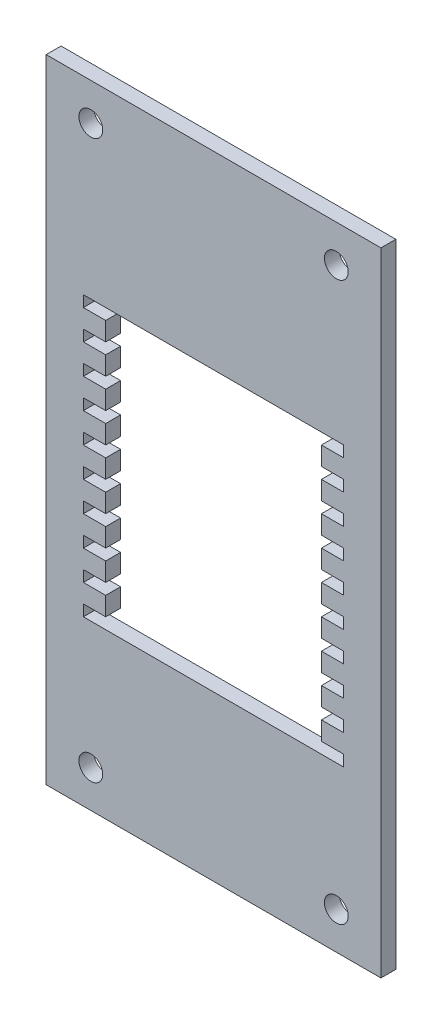
SolidWorks part; units mm, degrees
ref_plane "Ebene vorne" through (0, 0, 0) normal (0, 0, 1) x (1, 0, 0)
ref_plane "Ebene oben" through (0, 0, 0) normal (0, 1, 0) x (1, 0, 0)
ref_plane "Ebene rechts" through (0, 0, 0) normal (1, 0, 0) x (0, 0, -1)
sketch "Skizze1" plane through (0, 0, 0) normal (0, 0, 1) x (1, 0, 0)
  line L1 (0, 0) -> (45, 0)
  line L2 (0, 0) -> (0, 85)
  line L3 (0, 85) -> (45, 85)
  line L4 (45, 0) -> (45, 85)
  dimension "D1" = 45
  dimension "D2" = 85
extrude "Aufsatz-Linear austragen1" add sketch "Skizze1" along normal blind 2
sketch "Skizze6" plane through (0, 0, 2) normal (0, 0, 1) x (1, 0, 0)
  line L0 (0, 85) -> (0, 0) construction
  line L1 (45, 85) -> (0, 85) construction
  line L2 (45, 0) -> (45, 85) construction
  line L3 (0, 0) -> (45, 0) construction
  circle A0 centre (6, 80) radius 1.6
  circle A1 centre (39, 80) radius 1.6
  circle A2 centre (39, 5) radius 1.6
  circle A3 centre (6, 5) radius 1.6
  dimension "D8" = 6
  dimension "D9" = 3.2
  dimension "D10" = 3.2
  dimension "D11" = 3.2
  dimension "D12" = 3.2
  dimension "D1" = 6
  dimension "D2" = 5
  dimension "D3" = 5
  dimension "D4" = 6
  dimension "D5" = 5
  dimension "D6" = 6
  dimension "D7" = 5
extrude "Schnitt-Linear austragen2" cut sketch "Skizze6" against normal blind 2
sketch "Skizze7" plane through (0, 0, 2) normal (0, 0, 1) x (1, 0, 0)
  line L0 (45, 85) -> (0, 85) construction
  line L1 (5, 59.55) -> (40, 59.55)
  line L2 (5, 59.55) -> (5, 58.05)
  line L3 (5, 58.05) -> (40, 58.05)
  line L4 (40, 59.55) -> (40, 58.05)
  line L5 (45, 0) -> (45, 85) construction
  line L7 (5, 55.55) -> (40, 55.55)
  line L8 (5, 55.55) -> (5, 54.05)
  line L9 (5, 54.05) -> (40, 54.05)
  line L10 (40, 55.55) -> (40, 54.05)
  line L11 (5, 51.55) -> (40, 51.55)
  line L12 (5, 51.55) -> (5, 50.05)
  line L13 (5, 50.05) -> (40, 50.05)
  line L14 (40, 51.55) -> (40, 50.05)
  line L15 (5, 47.55) -> (40, 47.55)
  line L16 (5, 47.55) -> (5, 46.05)
  line L17 (5, 46.05) -> (40, 46.05)
  line L18 (40, 47.55) -> (40, 46.05)
  line L19 (5, 43.55) -> (40, 43.55)
  line L20 (5, 43.55) -> (5, 42.05)
  line L21 (5, 42.05) -> (40, 42.05)
  line L22 (40, 43.55) -> (40, 42.05)
  line L23 (5, 39.55) -> (40, 39.55)
  line L24 (5, 39.55) -> (5, 38.05)
  line L25 (5, 38.05) -> (40, 38.05)
  line L26 (40, 39.55) -> (40, 38.05)
  line L27 (5, 35.55) -> (40, 35.55)
  line L28 (5, 35.55) -> (5, 34.05)
  line L29 (5, 34.05) -> (40, 34.05)
  line L30 (40, 35.55) -> (40, 34.05)
  line L31 (5, 31.55) -> (40, 31.55)
  line L32 (5, 31.55) -> (5, 30.05)
  line L33 (5, 30.05) -> (40, 30.05)
  line L34 (40, 31.55) -> (40, 30.05)
  line L35 (5, 27.55) -> (40, 27.55)
  line L36 (5, 27.55) -> (5, 26.05)
  line L37 (5, 26.05) -> (40, 26.05)
  line L38 (40, 27.55) -> (40, 26.05)
  line L39 (5, 23.55) -> (40, 23.55)
  line L40 (5, 23.55) -> (5, 22.05)
  line L41 (5, 22.05) -> (40, 22.05)
  line L42 (40, 23.55) -> (40, 22.05)
  dimension "D1" = 25.45
  dimension "D2" = 1.5
  dimension "D3" = 5
  dimension "D4" = 35
  dimension "D5" = 2.5
  dimension "D6" = 1.5
  dimension "D7" = 2.5
  dimension "D8" = 1.5
  dimension "D9" = 2.5
  dimension "D10" = 1.5
  dimension "D11" = 2.5
  dimension "D12" = 1.5
  dimension "D13" = 2.5
  dimension "D14" = 1.5
  dimension "D15" = 2.5
  dimension "D16" = 1.5
  dimension "D17" = 2.5
  dimension "D18" = 1.5
  dimension "D19" = 2.5
  dimension "D20" = 1.5
  dimension "D21" = 2.5
  dimension "D22" = 1.5
extrude "Schnitt-Linear austragen3" cut sketch "Skizze7" against normal blind 10
sketch "Skizze8" plane through (0, 0, 2) normal (0, 0, 1) x (1, 0, 0)
  line L0 (40, 59.55) -> (5, 59.55) construction
  line L1 (8, 59.55) -> (37, 59.55)
  line L2 (8, 59.55) -> (8, 22.05)
  line L3 (8, 22.05) -> (37, 22.05)
  line L4 (37, 59.55) -> (37, 22.05)
  line L5 (5, 22.05) -> (40, 22.05) construction
  line L6 (40, 58.05) -> (40, 59.55) construction
  line L7 (5, 43.55) -> (5, 42.05) construction
  dimension "D1" = 3
  dimension "D2" = 3
extrude "Schnitt-Linear austragen4" cut sketch "Skizze8" against normal blind 10
